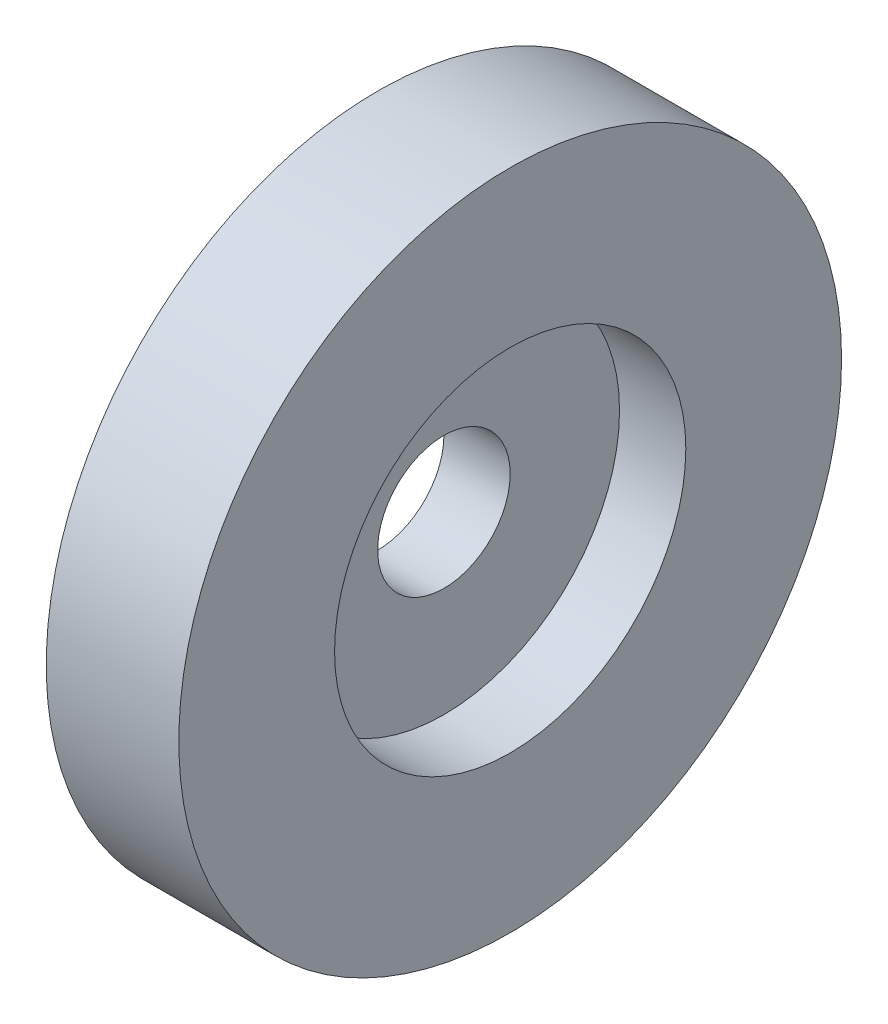
SolidWorks part; units mm, degrees
ref_plane "前视基准面" through (0, 0, 0) normal (0, 0, 1) x (1, 0, 0)
ref_plane "上视基准面" through (0, 0, 0) normal (0, 1, 0) x (1, 0, 0)
ref_plane "右视基准面" through (0, 0, 0) normal (1, 0, 0) x (0, 0, -1)
other "Configuration Table"
sketch "草图1" plane through (0, 0, 0) normal (1, 0, 0) x (0, 0, -1)
  circle A0 centre (0, 0) radius 10
  dimension "D1" = 20
extrude "凸台-拉伸1" add sketch "草图1" along normal blind 4
sketch "草图2" plane through (4, 0, 0) normal (1, 0, 0) x (0, 0, -1)
  circle A0 centre (0, 0) radius 2
  dimension "D1" = 4
extrude "切除-拉伸1" cut sketch "草图2" against normal up to surface (4 mm away) up to face at (0, 0, -10)
sketch "草图4" plane through (4, 0, 0) normal (1, 0, 0) x (0, 0, -1)
  circle A0 centre (0, 0) radius 5.3
  dimension "D1" = 10.6
extrude "切除-拉伸3" cut sketch "草图4" against normal blind 2
